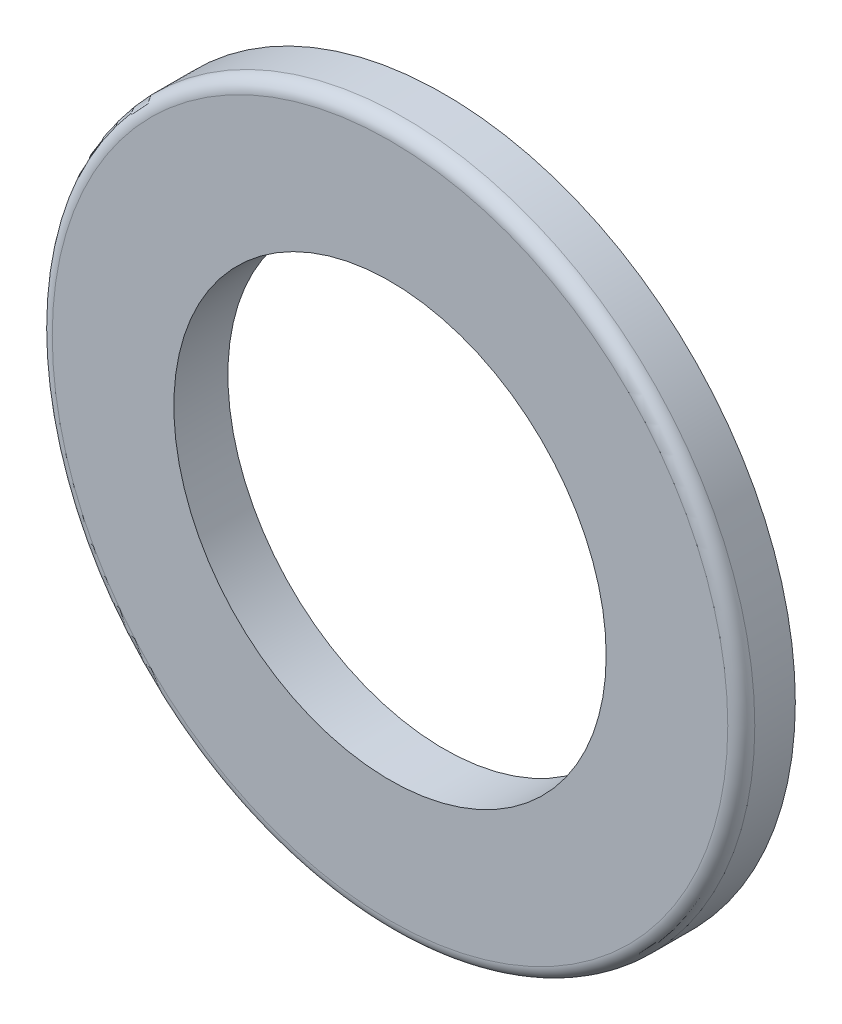
SolidWorks part; units mm, degrees
ref_plane "Front Plane" through (0, 0, 0) normal (0, 0, 1) x (1, 0, 0)
ref_plane "Top Plane" through (0, 0, 0) normal (0, 1, 0) x (1, 0, 0)
ref_plane "Right Plane" through (0, 0, 0) normal (1, 0, 0) x (0, 0, -1)
sketch "Sketch1" plane through (0, 0, 0) normal (0, 0, 1) x (1, 0, 0)
  circle A1 centre (0, 0) radius 13
  circle A2 centre (0, 0) radius 8
  dimension "D1" = 5
  dimension "D3" = 16
extrude "Boss-Extrude1" add sketch "Sketch1" along normal blind 2 contours A1 | A2
fillet "Fillet1" radius 0.5 1 edges at (13, 0, 2)
